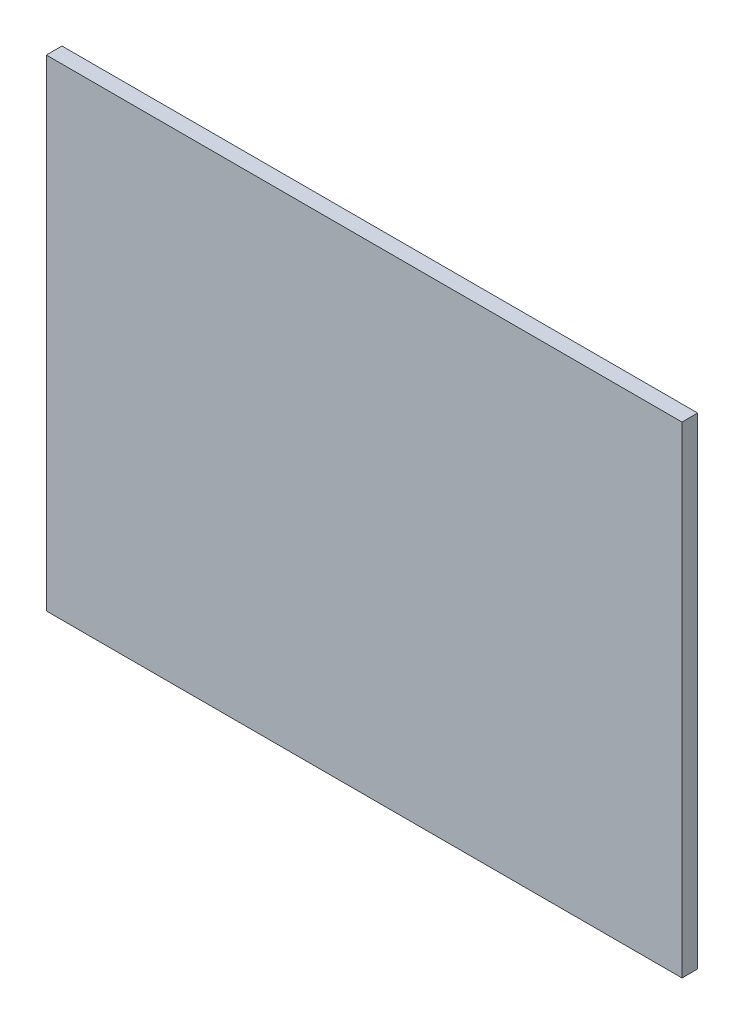
SolidWorks part; units mm, degrees
ref_plane "Front Plane" through (0, 0, 0) normal (0, 0, 1) x (1, 0, 0)
ref_plane "Top Plane" through (0, 0, 0) normal (0, 1, 0) x (1, 0, 0)
ref_plane "Right Plane" through (0, 0, 0) normal (1, 0, 0) x (0, 0, -1)
sketch "Sketch1" plane through (0, 0, 0) normal (0, 0, 1) x (1, 0, 0)
  line L1 (206.3688, -412.7201) -> (-206.5, -412.7201)
  line L2 (206.3688, -412.7201) -> (206.3688, -100.0201)
  line L3 (206.3688, -100.0201) -> (-206.5, -100.0201)
  line L4 (-206.5, -412.7201) -> (-206.5, -100.0201)
  point P4 (0, 0)
  dimension "D1" = 312.7
extrude "Boss-Extrude1" add sketch "Sketch1" against normal blind 10.16
